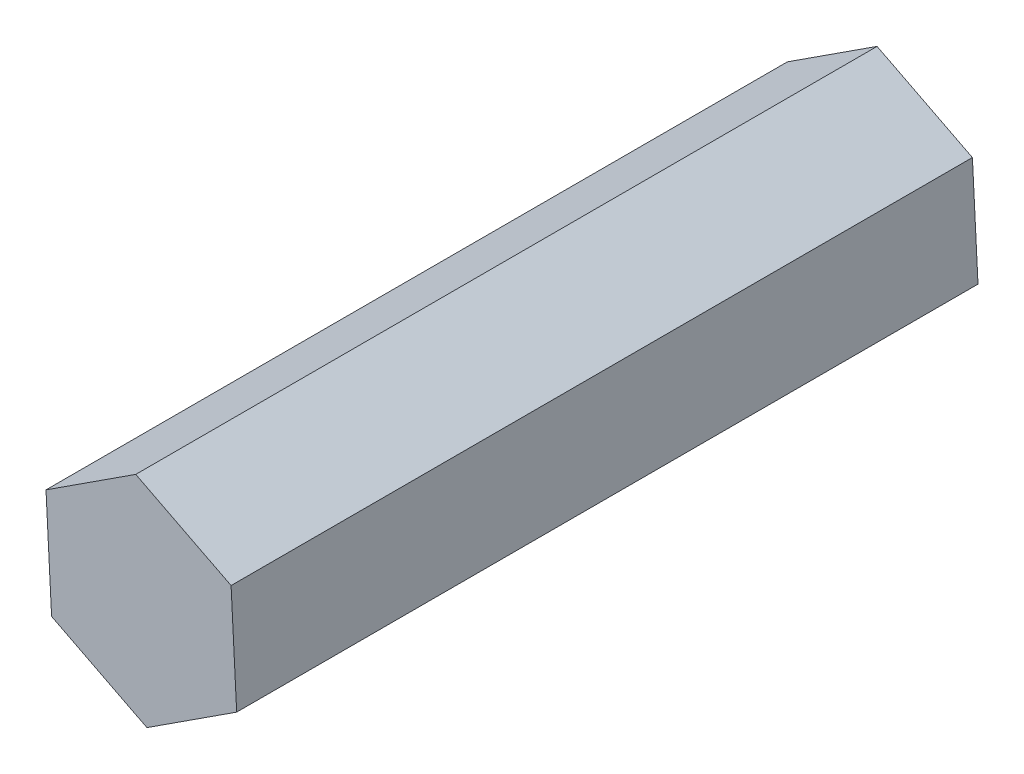
SolidWorks part; units mm, degrees
ref_plane "Front Plane" through (0, 0, 0) normal (0, 0, 1) x (1, 0, 0)
ref_plane "Top Plane" through (0, 0, 0) normal (0, 1, 0) x (1, 0, 0)
ref_plane "Right Plane" through (0, 0, 0) normal (1, 0, 0) x (0, 0, -1)
sketch "Sketch2" plane through (0, 0, 0) normal (0, 0, 1) x (1, 0, 0)
  line L1 (-6.5329, 3.3293) -> (-6.1497, -3.993)
  line L2 (-6.1497, -3.993) -> (0.3832, -7.3223)
  line L3 (0.3832, -7.3223) -> (6.5329, -3.3293)
  line L4 (6.5329, -3.3293) -> (6.1497, 3.993)
  line L5 (6.1497, 3.993) -> (-0.3832, 7.3223)
  line L6 (-0.3832, 7.3223) -> (-6.5329, 3.3293)
  circle A0 centre (0, 0) radius 6.35 construction
  point P1 (6.3413, 0.3319)
  dimension "D1" = 12.7
extrude "Boss-Extrude2" add sketch "Sketch2" along normal blind 50.8
sketch "Sketch3" plane through (0, 0, 50.8) normal (0, 0, 1) x (1, 0, 0)
  circle A0 centre (0, 0) radius 6.35
  dimension "D1" = 12.7
equation "\"4n\"=3.75"
